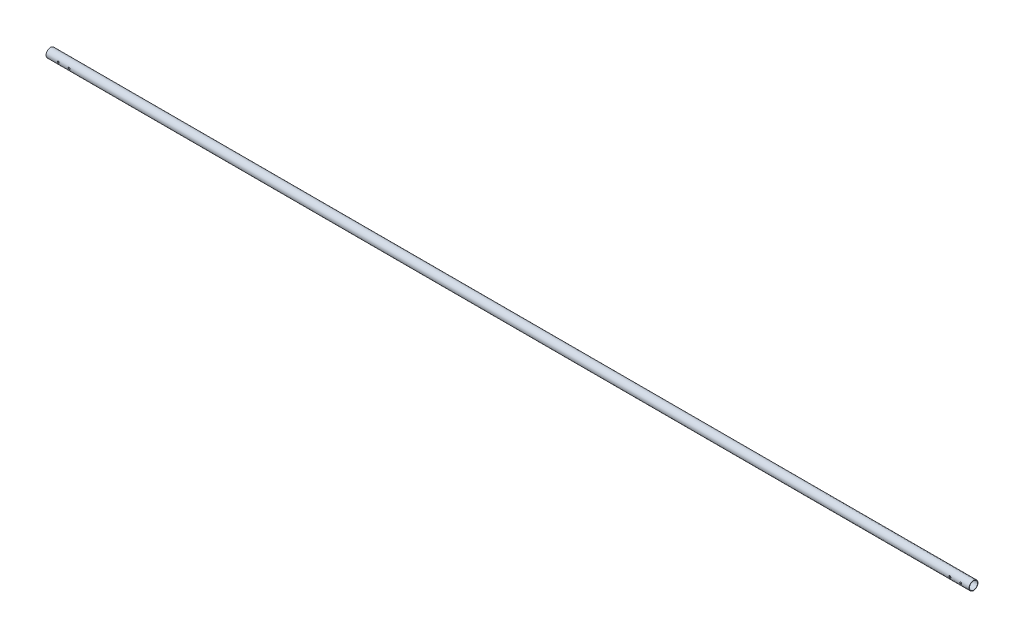
SolidWorks part; units mm, degrees
material "Galvanized Steel"
ref_plane "Front Plane" through (0, 0, 0) normal (0, 0, 1) x (1, 0, 0)
ref_plane "Top Plane" through (0, 0, 0) normal (0, 1, 0) x (1, 0, 0)
ref_plane "Right Plane" through (0, 0, 0) normal (1, 0, 0) x (0, 0, -1)
sketch "Sketch3" plane through (0, 0, 0) normal (1, 0, 0) x (0, 0, -1)
  circle A0 centre (0, 0) radius 13.3223
  circle A1 centre (0, 0) radius 14.7701
  dimension "D1" = 26.6446
  dimension "D2" = 29.5402
extrude "Boss-Extrude1" add sketch "Sketch3" along normal blind 3048
sketch "Sketch4" plane through (0, 0, 0) normal (0, 0, 1) x (1, 0, 0)
  line L0 (3048, -14.7701) -> (3048, 14.7701) construction
  line L2 (0, 14.7701) -> (0, -14.7701) construction
  circle A0 centre (40.386, 0) radius 3.175
  circle A1 centre (76.2, 0) radius 3.175
  circle A2 centre (3020.314, 0) radius 3.175
  circle A3 centre (2984.5, 0) radius 3.175
  dimension "D1" = 27.686
  dimension "D2" = 35.814
  dimension "D3" = 2908.3
  dimension "D4" = 35.814
  dimension "D5" = 40.386
extrude "Cut-Extrude1" cut sketch "Sketch4" against normal through all and the other way through all
